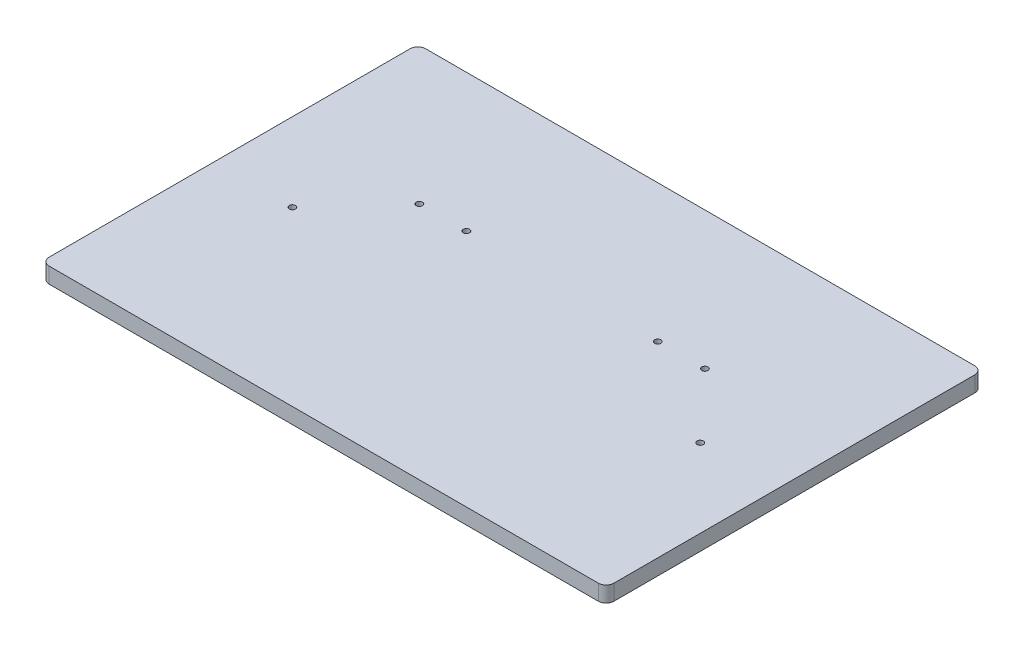
SolidWorks part; units mm, degrees
ref_plane "Front Plane" through (0, 0, 0) normal (0, 0, 1) x (1, 0, 0)
ref_plane "Top Plane" through (0, 0, 0) normal (0, 1, 0) x (1, 0, 0)
ref_plane "Right Plane" through (0, 0, 0) normal (1, 0, 0) x (0, 0, -1)
sketch "Sketch1" plane through (0, 0, 0) normal (0, 1, 0) x (1, 0, 0)
  line L1 (222.25, 152.4) -> (-222.25, 152.4)
  line L2 (228.6, 146.05) -> (228.6, -146.05)
  line L3 (222.25, -152.4) -> (-222.25, -152.4)
  line L4 (-228.6, 146.05) -> (-228.6, -146.05)
  arc A0 (-222.25, 152.4) -> (-228.6, 146.05) centre (-222.25, 146.05) ccw
  arc A1 (222.25, 152.4) -> (228.6, 146.05) centre (222.25, 146.05) cw
  arc A2 (228.6, -146.05) -> (222.25, -152.4) centre (222.25, -146.05) cw
  arc A3 (-222.25, -152.4) -> (-228.6, -146.05) centre (-222.25, -146.05) cw
  circle A4 centre (-165.1, -12.7) radius 2.54
  circle A5 centre (165.1, -12.7) radius 2.54
  point P0 (0, 0)
  dimension "D1" = 6.35
  dimension "D2" = 6.35
  dimension "D3" = 6.35
  dimension "D4" = 6.35
extrude "Boss-Extrude1" add sketch "Sketch1" along normal blind 12.7
sketch "Sketch2" plane through (0, 12.7, 0) normal (0, 1, 0) x (1, 0, 0)
  circle A0 centre (-116.0653, 41.0459) radius 2.54
  circle A1 centre (-77.9653, 41.0459) radius 2.54
  circle A2 centre (76.9747, 41.0459) radius 2.54
  circle A3 centre (115.0747, 41.0459) radius 2.54
extrude "Cut-Extrude1" cut sketch "Sketch2" against normal blind 12.7
